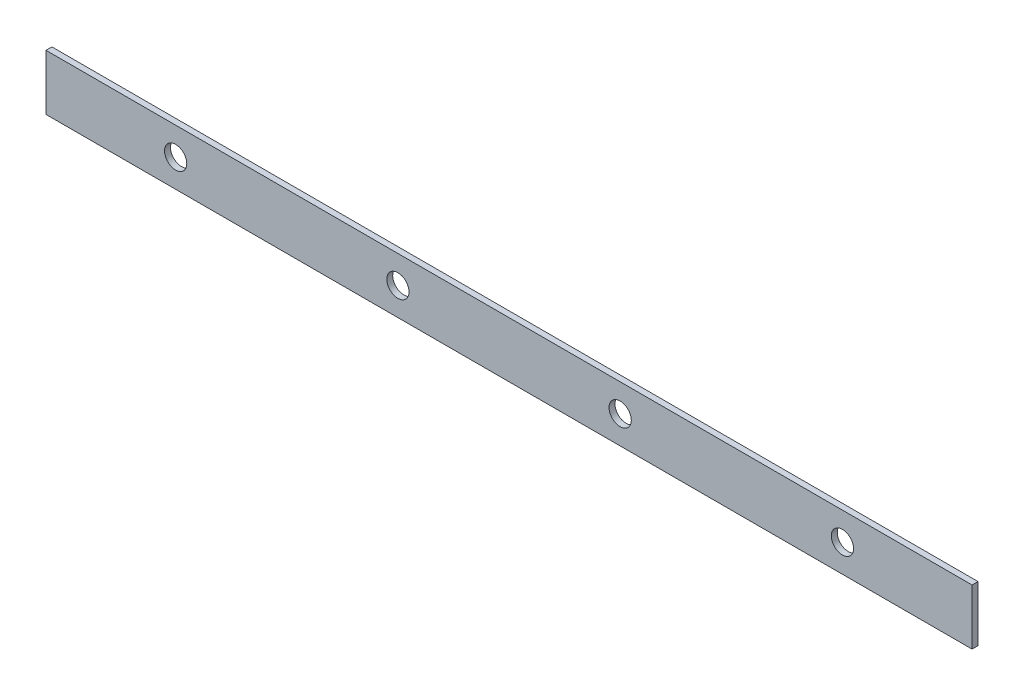
SolidWorks part; units mm, degrees
ref_plane "Спереди" through (0, 0, 0) normal (0, 0, 1) x (1, 0, 0)
ref_plane "Сверху" through (0, 0, 0) normal (0, 1, 0) x (1, 0, 0)
ref_plane "Справа" through (0, 0, 0) normal (1, 0, 0) x (0, 0, -1)
sketch "Model" plane through (0, 0, 0) normal (0, 0, 1) x (1, 0, 0)
  line L0 (0, 0) -> (250, 0)
  line L1 (250, 15) -> (250, 0)
  line L2 (250, 15) -> (0, 15)
  line L3 (0, 15) -> (0, 0)
  line L4 (35, 7.5) -> (95, 7.5) construction
  line L5 (95, 7.5) -> (155, 7.5) construction
  line L6 (155, 7.5) -> (215, 7.5) construction
  line L7 (125, 0) -> (125, 7.5) construction
  line L8 (125, 7.5) -> (125, 15) construction
  circle A0 centre (215, 7.5) radius 3
  circle A1 centre (95, 7.5) radius 3
  circle A2 centre (35, 7.5) radius 3
  circle A3 centre (155, 7.5) radius 3
  dimension "D3" = 6
  dimension "D1" = 15
  dimension "D2" = 250
  dimension "D4" = 180
extrude "Бобышка-Вытянуть1" add sketch "Model" against normal blind 1.6
